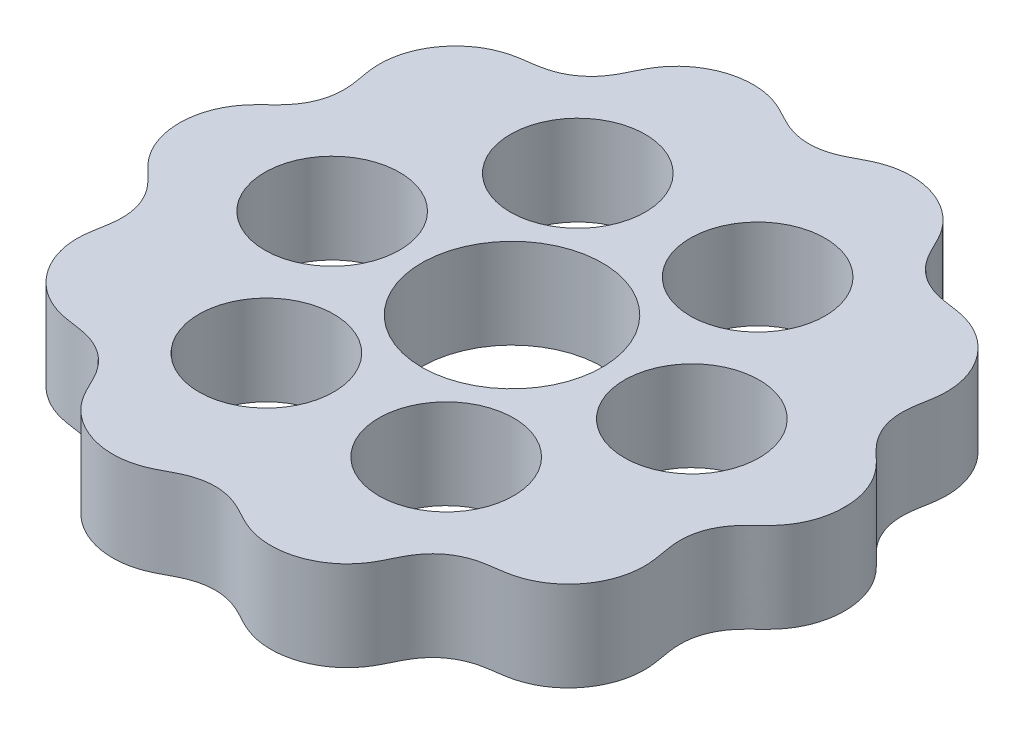
SolidWorks part; units mm, degrees
ref_plane "Front Plane" through (0, 0, 0) normal (0, 0, 1) x (1, 0, 0)
ref_plane "Top Plane" through (0, 0, 0) normal (0, 1, 0) x (1, 0, 0)
ref_plane "Right Plane" through (0, 0, 0) normal (1, 0, 0) x (0, 0, -1)
sketch "Sketch3" plane through (0, 0, 0) normal (0, 1, 0) x (1, 0, 0)
  line L0 (37, 0.0016) -> (37, 0)
  circle A8 centre (0, 0) radius 10.05
  circle A9 centre (20, 0.0013) radius 7.5
  circle A10 centre (10.0011, -17.3198) radius 7.5
  circle A11 centre (-9.9989, -17.3212) radius 7.5
  circle A12 centre (-20, -0.0013) radius 7.5
  circle A13 centre (-10.0011, 17.3198) radius 7.5
  circle A14 centre (9.9989, 17.3212) radius 7.5
  spline S0 degree 4 poles (35.9071, -20.9058) (35.9914, -20.646) (36.1459, -20.1219) (36.3345, -19.3236) (36.4974, -18.2422) (36.5702, -17.151) (36.5533, -16.0577) (36.455, -15.0177) (36.3162, -14.1457) (36.1841, -13.4361) (36.0999, -12.9253) (36.0584, -12.5653) (36.0496, -12.2224) (36.083, -11.8936) (36.188, -11.5721) (36.3627, -11.2777) (36.5928, -10.9853) (36.8654, -10.6961) (37.1851, -10.385) (37.5433, -10.0427) (38.0155, -9.5807) (38.5864, -8.9833) (39.2264, -8.2247) (39.8954, -7.2794) (40.3957, -6.4221) (40.7606, -5.6806) (41.0199, -5.0731) (41.1972, -4.6108) (41.3572, -4.1422) (41.4998, -3.6681) (41.6249, -3.1888) (41.7323, -2.7057) (41.8219, -2.2182) (41.8937, -1.7291) (41.9408, -1.2971) (41.97, -0.9276) (41.9852, -0.6533) (41.9925, -0.4614) (41.9976, -0.2622) (42.0004, -0.0689) (42.0004, 0.0868) (41.995, 0.4231) (41.98, 0.7903) (41.95, 1.2044) (41.8985, 1.6906) (41.83, 2.1667) (41.7445, 2.6443) (41.642, 3.1162) (41.5226, 3.5855) (41.3864, 4.0495) (41.2336, 4.5086) (41.0642, 4.9618) (40.8785, 5.4086) (40.6767, 5.8483) (40.4044, 6.3882) (40.0465, 7.0195) (39.5845, 7.7294) (38.9992, 8.5005) (38.3617, 9.229) (37.7471, 9.8506) (37.2345, 10.3361) (36.8495, 10.7125) (36.5753, 11.0078) (36.3656, 11.2699) (36.1909, 11.5665) (36.0759, 11.9257) (36.0454, 12.2689) (36.0624, 12.6048) (36.1118, 13.0057) (36.2028, 13.5376) (36.3321, 14.2334) (36.5001, 15.3392) (36.5994, 16.7927) (36.5088, 18.4932) (36.1215, 20.4) (35.4619, 22.2306) (34.5487, 23.946) (33.4033, 25.5131) (32.0493, 26.9009) (30.5132, 28.0808) (28.8229, 29.0266) (27.2386, 29.6295) (25.8309, 29.9783) (24.732, 30.1572) (24.0335, 30.2485) (23.5021, 30.327) (23.1077, 30.4056) (22.7852, 30.4957) (22.4708, 30.6351) (22.1686, 30.8608) (21.9438, 31.1223) (21.7609, 31.4055) (21.5656, 31.7601) (21.3266, 32.2452) (21.0213, 32.8855) (20.5051, 33.8807) (19.7274, 35.1165) (18.6497, 36.4399) (17.2094, 37.7547) (15.5934, 38.8465) (13.8338, 39.6976) (11.9667, 40.2905) (10.0292, 40.6113) (8.0612, 40.6482) (6.1086, 40.3964) (4.2154, 39.8563) (2.8138, 39.2258) (1.8483, 38.6935) (1.2513, 38.3822) (1.032, 38.2755) (0.7714, 38.1602) (0.4829, 38.0573) (0.1615, 37.9911) (-0.2151, 37.9987) (-0.5569, 38.0826) (-0.8789, 38.2097) (-1.259, 38.3909) (-1.7487, 38.6507) (-2.3805, 38.9927) (-3.389, 39.4921) (-4.7434, 40.0264) (-6.3905, 40.4541) (-8.324, 40.662) (-10.267, 40.5877) (-12.1841, 40.2363) (-14.0364, 39.6143) (-15.7856, 38.7323) (-17.393, 37.6039) (-18.8184, 36.2525) (-20.0268, 34.7041) (-20.7866, 33.3722) (-21.2531, 32.376) (-21.5803, 31.7205) (-21.7459, 31.4177) (-21.9435, 31.1084) (-22.208, 30.823) (-22.5189, 30.6105) (-22.846, 30.4795) (-23.1822, 30.3942) (-23.5974, 30.3181) (-24.1476, 30.2408) (-24.8613, 30.1456) (-25.9731, 29.9553) (-27.3855, 29.5884) (-28.9719, 28.9619) (-30.6599, 27.9876) (-32.1887, 26.7789) (-33.5306, 25.3624) (-34.6589, 23.7673) (-35.5496, 22.0251) (-36.181, 20.1701) (-36.5342, 18.2427) (-36.5909, 16.5288) (-36.4614, 15.0677) (-36.2805, 13.9849) (-36.1453, 13.2666) (-36.0602, 12.6842) (-36.0373, 12.2577) (-36.0858, 11.8743) (-36.2126, 11.5271) (-36.3935, 11.2391) (-36.6032, 10.9847) (-36.8748, 10.6964) (-37.2539, 10.3275) (-37.757, 9.8502) (-38.5279, 9.0704) (-39.4468, 7.9773) (-40.3619, 6.5813) (-41.1674, 4.8523) (-41.7186, 3.0266) (-42.01, 1.1315) (-42.0333, -0.7962) (-41.7832, -2.7182) (-41.258, -4.595) (-40.4662, -6.376) (-39.5519, -7.8159) (-38.6257, -8.9435) (-37.8386, -9.7515) (-37.3174, -10.2484) (-36.918, -10.6346) (-36.627, -10.9404) (-36.4053, -11.2071) (-36.2178, -11.5055) (-36.0914, -11.8602) (-36.0454, -12.2466) (-36.0675, -12.613) (-36.1117, -12.9552) (-36.2327, -13.6777) (-36.4416, -14.7577) (-36.6107, -16.2817) (-36.5445, -18.2447) (-36.1869, -20.1761) (-35.5509, -22.0341) (-34.6553, -23.7764) (-33.5235, -25.369) (-32.18, -26.7811) (-30.6525, -27.9842) (-28.9667, -28.9537) (-27.3831, -29.5768) (-25.9735, -29.9416) (-24.8642, -30.1311) (-24.152, -30.2262) (-23.6032, -30.3041) (-23.1892, -30.3812) (-22.854, -30.4678) (-22.5282, -30.6011) (-22.2193, -30.8165) (-21.9568, -31.1044) (-21.7603, -31.4152) (-21.5952, -31.7192) (-21.2684, -32.3767) (-20.8008, -33.3751) (-20.0383, -34.7095) (-18.8252, -36.26) (-17.3944, -37.6123) (-15.7813, -38.7402) (-14.0259, -39.6207) (-12.1673, -40.2397) (-10.2437, -40.5866) (-8.2946, -40.6545) (-6.3564, -40.4386) (-4.7063, -40.0025) (-3.3503, -39.4606) (-2.3475, -38.9596) (-1.7239, -38.6214) (-1.2451, -38.3697) (-0.8786, -38.1978) (-0.5642, -38.0764) (-0.2285, -37.9972) (0.1487, -37.9924) (0.4849, -38.0646) (0.7987, -38.1815) (1.1638, -38.3499) (1.6397, -38.5991) (2.2582, -38.9361) (3.2522, -39.4379) (4.5956, -39.984) (6.2314, -40.4285) (8.1546, -40.6581) (10.0908, -40.6077) (12.0022, -40.282) (13.8503, -39.6888) (15.598, -38.8388) (17.2084, -37.7465) (18.6434, -36.4324) (19.717, -35.1106) (20.4919, -33.8769) (21.0065, -32.8838) (21.3114, -32.245) (21.5506, -31.7614) (21.7465, -31.4081) (21.9304, -31.1265) (22.157, -30.8669) (22.4613, -30.644) (22.777, -30.507) (23.1007, -30.4183) (23.4962, -30.3408) (24.0289, -30.263) (24.7291, -30.1718) (25.8304, -29.9921) (27.241, -29.6412) (28.8281, -29.035) (30.5207, -28.0844) (32.0581, -26.899) (33.4107, -25.5067) (34.5526, -23.9371) (35.4611, -22.2216) (36.1158, -20.394) (36.4992, -18.4908) (36.5875, -16.7941) (36.4872, -15.344) (36.3191, -14.2407) (36.1904, -13.5464) (36.1004, -13.0156) (36.0524, -12.6154) (36.0371, -12.2802) (36.0702, -11.9376) (36.1886, -11.5794) (36.3657, -11.2839) (36.5771, -11.0223) (36.8529, -10.7272) (37.2393, -10.3505) (37.7533, -9.8641) (38.3691, -9.2409) (39.0075, -8.5102) (39.5933, -7.7369) (40.1214, -6.9231) (40.53, -6.1789) (40.8406, -5.521) (41.0723, -4.9609) (41.2413, -4.5065) (41.3937, -4.046) (41.5293, -3.5807) (41.648, -3.1102) (41.7498, -2.6369) (41.8345, -2.1581) (41.9022, -1.6808) (41.9527, -1.1934) (41.9818, -0.7782) (41.996, -0.4104) (42.0005, -0.0748) (42.0001, 0.1017) (41.9939, 0.436) (41.9781, 0.8027) (41.9472, 1.2157) (41.8947, 1.7009) (41.8253, 2.1759) (41.7389, 2.6524) (41.6357, 3.1232) (41.5156, 3.5913) (41.3788, 4.0541) (41.2254, 4.512) (41.0556, 4.9639) (40.8229, 5.5209) (40.5116, 6.175) (40.1025, 6.9149) (39.5743, 7.724) (38.9892, 8.4929) (38.3522, 9.2194) (37.7385, 9.8395) (37.2271, 10.3241) (36.8436, 10.7005) (36.571, 10.9963) (36.3634, 11.2592) (36.1856, 11.5678) (36.086, 11.905) (36.0574, 12.2165) (36.0688, 12.5602) (36.1119, 12.9211) (36.1975, 13.433) (36.3302, 14.1445) (36.4688, 15.019) (36.5661, 16.0618) (36.5813, 17.1582) (36.5063, 18.2522) (36.3407, 19.3362) (36.1497, 20.1362) (35.9935, 20.6613) (35.9084, 20.9216) knots 0 0 0 0 0 0.003453 0.006906 0.010359 0.013812 0.017264 0.020716 0.023554 0.024972 0.026391 0.027261 0.028132 0.029304 0.030549 0.031493 0.032437 0.034003 0.035569 0.037134 0.0387 0.042356 0.046012 0.049669 0.053325 0.05489 0.056454 0.058019 0.059584 0.061149 0.062713 0.064278 0.065843 0.067408 0.068973 0.069755 0.070538 0.070929 0.07132 0.072103 0.072867 0.073631 0.07516 0.076689 0.078218 0.079746 0.081275 0.082804 0.084333 0.085862 0.087391 0.08892 0.090449 0.091978 0.093506 0.096564 0.09962 0.102677 0.105736 0.108794 0.110668 0.111605 0.112542 0.113887 0.114906 0.115926 0.117275 0.118214 0.119153 0.121031 0.124097 0.127162 0.133289 0.139418 0.145548 0.151677 0.157806 0.163906 0.170007 0.17611 0.182211 0.188311 0.191362 0.194413 0.196283 0.197218 0.198153 0.199495 0.200511 0.201534 0.202886 0.203827 0.204768 0.20665 0.209723 0.212796 0.218936 0.225079 0.231223 0.237366 0.243508 0.249708 0.255908 0.262109 0.268309 0.274508 0.280708 0.281479 0.282249 0.28302 0.283791 0.285081 0.286117 0.28714 0.288515 0.289502 0.290489 0.292462 0.295524 0.298586 0.304711 0.310837 0.316961 0.323086 0.329211 0.335397 0.341582 0.34777 0.353955 0.36014 0.366326 0.367095 0.367864 0.369402 0.370689 0.371723 0.372748 0.374127 0.375115 0.376104 0.378082 0.381151 0.38422 0.390359 0.396498 0.402637 0.408775 0.414914 0.421085 0.427257 0.43343 0.439601 0.445772 0.448858 0.451944 0.453478 0.455013 0.456297 0.457328 0.458329 0.459651 0.460572 0.461493 0.463334 0.466338 0.469341 0.475351 0.481359 0.487368 0.493376 0.499384 0.505523 0.511661 0.5178 0.523939 0.530079 0.533148 0.536217 0.538194 0.539183 0.540172 0.541551 0.542576 0.543609 0.544897 0.546435 0.547204 0.547972 0.554158 0.560343 0.566529 0.572716 0.578901 0.585087 0.591212 0.597337 0.603461 0.609587 0.615712 0.618774 0.621837 0.62381 0.624796 0.625783 0.627159 0.628182 0.629217 0.630508 0.632049 0.63282 0.63359 0.639791 0.64599 0.652189 0.65839 0.66459 0.670789 0.676932 0.683075 0.689219 0.695362 0.701502 0.704575 0.707648 0.709531 0.710472 0.711413 0.712764 0.713787 0.714804 0.716146 0.717081 0.718015 0.719885 0.722936 0.725988 0.732088 0.738188 0.74429 0.750391 0.756492 0.762621 0.76875 0.77488 0.781009 0.787136 0.790202 0.793268 0.795146 0.796085 0.797024 0.798372 0.799393 0.800412 0.801757 0.802694 0.803631 0.805504 0.808563 0.811621 0.817735 0.823849 0.829965 0.83608 0.842195 0.84831 0.854425 0.860541 0.866656 0.87277 0.875828 0.878887 0.880761 0.881698 0.882635 0.88398 0.884999 0.886019 0.887368 0.888307 0.889246 0.891124 0.89419 0.897255 0.900318 0.903382 0.906446 0.90951 0.911043 0.912575 0.914108 0.91564 0.917172 0.918705 0.920237 0.921769 0.923301 0.924833 0.926365 0.927132 0.927898 0.92866 0.929423 0.930949 0.932475 0.934001 0.935526 0.937052 0.938578 0.940104 0.94163 0.943155 0.944681 0.946207 0.949259 0.95231 0.955362 0.958413 0.961465 0.964517 0.966388 0.967323 0.968258 0.969601 0.970617 0.971792 0.972665 0.973538 0.97496 0.976383 0.979228 0.982689 0.986151 0.989613 0.993075 0.996538 1 1 1 1 1 construction
  spline S1 degree 4 poles (42, 0) (42, 0.0517) (41.9993, 0.1553) (41.995, 0.4231) (41.98, 0.7903) (41.95, 1.2044) (41.8985, 1.6906) (41.83, 2.1667) (41.7445, 2.6443) (41.642, 3.1162) (41.5226, 3.5855) (41.3864, 4.0495) (41.2336, 4.5086) (41.0642, 4.9618) (40.8785, 5.4086) (40.6767, 5.8483) (40.4044, 6.3882) (40.0465, 7.0195) (39.5845, 7.7294) (38.9992, 8.5005) (38.3617, 9.229) (37.7471, 9.8506) (37.2345, 10.3361) (36.8495, 10.7125) (36.5753, 11.0078) (36.3656, 11.2699) (36.1909, 11.5665) (36.0759, 11.9257) (36.0454, 12.2689) (36.0624, 12.6048) (36.1118, 13.0057) (36.2028, 13.5376) (36.3321, 14.2334) (36.5001, 15.3392) (36.5994, 16.7927) (36.5088, 18.4932) (36.1215, 20.4) (35.4619, 22.2306) (34.5487, 23.946) (33.4033, 25.5131) (32.0493, 26.9009) (30.5132, 28.0808) (28.8229, 29.0266) (27.2386, 29.6295) (25.8309, 29.9783) (24.732, 30.1572) (24.0335, 30.2485) (23.5021, 30.327) (23.1077, 30.4056) (22.7852, 30.4957) (22.4708, 30.6351) (22.1686, 30.8608) (21.9438, 31.1223) (21.7609, 31.4055) (21.5656, 31.7601) (21.3266, 32.2452) (21.0213, 32.8855) (20.5051, 33.8807) (19.7274, 35.1165) (18.6497, 36.4399) (17.2094, 37.7547) (15.5934, 38.8465) (13.8338, 39.6976) (11.9667, 40.2905) (10.0292, 40.6113) (8.0612, 40.6482) (6.1086, 40.3964) (4.2154, 39.8563) (2.8138, 39.2258) (1.8483, 38.6935) (1.2513, 38.3822) (1.032, 38.2755) (0.7714, 38.1602) (0.4829, 38.0573) (0.1615, 37.9911) (-0.2151, 37.9987) (-0.5569, 38.0826) (-0.8789, 38.2097) (-1.259, 38.3909) (-1.7487, 38.6507) (-2.3805, 38.9927) (-3.389, 39.4921) (-4.7434, 40.0264) (-6.3905, 40.4541) (-8.324, 40.662) (-10.267, 40.5877) (-12.1841, 40.2363) (-14.0364, 39.6143) (-15.7856, 38.7323) (-17.393, 37.6039) (-18.8184, 36.2525) (-20.0268, 34.7041) (-20.7866, 33.3722) (-21.2531, 32.376) (-21.5803, 31.7205) (-21.7459, 31.4177) (-21.9435, 31.1084) (-22.208, 30.823) (-22.5189, 30.6105) (-22.846, 30.4795) (-23.1822, 30.3942) (-23.5974, 30.3181) (-24.1476, 30.2408) (-24.8613, 30.1456) (-25.9731, 29.9553) (-27.3855, 29.5884) (-28.9719, 28.9619) (-30.6599, 27.9876) (-32.1887, 26.7789) (-33.5306, 25.3624) (-34.6589, 23.7673) (-35.5496, 22.0251) (-36.181, 20.1701) (-36.5342, 18.2427) (-36.5909, 16.5288) (-36.4614, 15.0677) (-36.2805, 13.9849) (-36.1453, 13.2666) (-36.0602, 12.6842) (-36.0373, 12.2577) (-36.0858, 11.8743) (-36.2126, 11.5271) (-36.3935, 11.2391) (-36.6032, 10.9847) (-36.8748, 10.6964) (-37.2539, 10.3275) (-37.757, 9.8502) (-38.5279, 9.0704) (-39.4468, 7.9773) (-40.3619, 6.5813) (-41.1674, 4.8523) (-41.7186, 3.0266) (-42.01, 1.1315) (-42.0333, -0.7962) (-41.7832, -2.7182) (-41.258, -4.595) (-40.4662, -6.376) (-39.5519, -7.8159) (-38.6257, -8.9435) (-37.8386, -9.7515) (-37.3174, -10.2484) (-36.918, -10.6346) (-36.627, -10.9404) (-36.4053, -11.2071) (-36.2178, -11.5055) (-36.0914, -11.8602) (-36.0454, -12.2466) (-36.0675, -12.613) (-36.1117, -12.9552) (-36.2327, -13.6777) (-36.4416, -14.7577) (-36.6107, -16.2817) (-36.5445, -18.2447) (-36.1869, -20.1761) (-35.5509, -22.0341) (-34.6553, -23.7764) (-33.5235, -25.369) (-32.18, -26.7811) (-30.6525, -27.9842) (-28.9667, -28.9537) (-27.3831, -29.5768) (-25.9735, -29.9416) (-24.8642, -30.1311) (-24.152, -30.2262) (-23.6032, -30.3041) (-23.1892, -30.3812) (-22.854, -30.4678) (-22.5282, -30.6011) (-22.2193, -30.8165) (-21.9568, -31.1044) (-21.7603, -31.4152) (-21.5952, -31.7192) (-21.2684, -32.3767) (-20.8008, -33.3751) (-20.0383, -34.7095) (-18.8252, -36.26) (-17.3944, -37.6123) (-15.7813, -38.7402) (-14.0259, -39.6207) (-12.1673, -40.2397) (-10.2437, -40.5866) (-8.2946, -40.6545) (-6.3564, -40.4386) (-4.7063, -40.0025) (-3.3503, -39.4606) (-2.3475, -38.9596) (-1.7239, -38.6214) (-1.2451, -38.3697) (-0.8786, -38.1978) (-0.5642, -38.0764) (-0.2285, -37.9972) (0.1487, -37.9924) (0.4849, -38.0646) (0.7987, -38.1815) (1.1638, -38.3499) (1.6397, -38.5991) (2.2582, -38.9361) (3.2522, -39.4379) (4.5956, -39.984) (6.2314, -40.4285) (8.1546, -40.6581) (10.0908, -40.6077) (12.0022, -40.282) (13.8503, -39.6888) (15.598, -38.8388) (17.2084, -37.7465) (18.6434, -36.4324) (19.717, -35.1106) (20.4919, -33.8769) (21.0065, -32.8838) (21.3114, -32.245) (21.5506, -31.7614) (21.7465, -31.4081) (21.9304, -31.1265) (22.157, -30.8669) (22.4613, -30.644) (22.777, -30.507) (23.1007, -30.4183) (23.4962, -30.3408) (24.0289, -30.263) (24.7291, -30.1718) (25.8304, -29.9921) (27.241, -29.6412) (28.8281, -29.035) (30.5207, -28.0844) (32.0581, -26.899) (33.4107, -25.5067) (34.5526, -23.9371) (35.4611, -22.2216) (36.1158, -20.394) (36.4992, -18.4908) (36.5875, -16.7941) (36.4872, -15.344) (36.3191, -14.2407) (36.1904, -13.5464) (36.1004, -13.0156) (36.0524, -12.6154) (36.0371, -12.2802) (36.0702, -11.9376) (36.1886, -11.5794) (36.3657, -11.2839) (36.5771, -11.0223) (36.8529, -10.7272) (37.2393, -10.3505) (37.7533, -9.8641) (38.3691, -9.2409) (39.0075, -8.5102) (39.5933, -7.7369) (40.1214, -6.9231) (40.53, -6.1789) (40.8406, -5.521) (41.0723, -4.9609) (41.2413, -4.5065) (41.3937, -4.046) (41.5293, -3.5807) (41.648, -3.1102) (41.7498, -2.6369) (41.8345, -2.1581) (41.9022, -1.6808) (41.9527, -1.1934) (41.9818, -0.7782) (41.996, -0.4104) (41.9996, -0.1417) (42.0001, -0.038) (42, 0.0138) knots 0.072103 0.072103 0.072103 0.072103 0.072103 0.072867 0.073631 0.07516 0.076689 0.078218 0.079746 0.081275 0.082804 0.084333 0.085862 0.087391 0.08892 0.090449 0.091978 0.093506 0.096564 0.09962 0.102677 0.105736 0.108794 0.110668 0.111605 0.112542 0.113887 0.114906 0.115926 0.117275 0.118214 0.119153 0.121031 0.124097 0.127162 0.133289 0.139418 0.145548 0.151677 0.157806 0.163906 0.170007 0.17611 0.182211 0.188311 0.191362 0.194413 0.196283 0.197218 0.198153 0.199495 0.200511 0.201534 0.202886 0.203827 0.204768 0.20665 0.209723 0.212796 0.218936 0.225079 0.231223 0.237366 0.243508 0.249708 0.255908 0.262109 0.268309 0.274508 0.280708 0.281479 0.282249 0.28302 0.283791 0.285081 0.286117 0.28714 0.288515 0.289502 0.290489 0.292462 0.295524 0.298586 0.304711 0.310837 0.316961 0.323086 0.329211 0.335397 0.341582 0.34777 0.353955 0.36014 0.366326 0.367095 0.367864 0.369402 0.370689 0.371723 0.372748 0.374127 0.375115 0.376104 0.378082 0.381151 0.38422 0.390359 0.396498 0.402637 0.408775 0.414914 0.421085 0.427257 0.43343 0.439601 0.445772 0.448858 0.451944 0.453478 0.455013 0.456297 0.457328 0.458329 0.459651 0.460572 0.461493 0.463334 0.466338 0.469341 0.475351 0.481359 0.487368 0.493376 0.499384 0.505523 0.511661 0.5178 0.523939 0.530079 0.533148 0.536217 0.538194 0.539183 0.540172 0.541551 0.542576 0.543609 0.544897 0.546435 0.547204 0.547972 0.554158 0.560343 0.566529 0.572716 0.578901 0.585087 0.591212 0.597337 0.603461 0.609587 0.615712 0.618774 0.621837 0.62381 0.624796 0.625783 0.627159 0.628182 0.629217 0.630508 0.632049 0.63282 0.63359 0.639791 0.64599 0.652189 0.65839 0.66459 0.670789 0.676932 0.683075 0.689219 0.695362 0.701502 0.704575 0.707648 0.709531 0.710472 0.711413 0.712764 0.713787 0.714804 0.716146 0.717081 0.718015 0.719885 0.722936 0.725988 0.732088 0.738188 0.74429 0.750391 0.756492 0.762621 0.76875 0.77488 0.781009 0.787136 0.790202 0.793268 0.795146 0.796085 0.797024 0.798372 0.799393 0.800412 0.801757 0.802694 0.803631 0.805504 0.808563 0.811621 0.817735 0.823849 0.829965 0.83608 0.842195 0.84831 0.854425 0.860541 0.866656 0.87277 0.875828 0.878887 0.880761 0.881698 0.882635 0.88398 0.884999 0.886019 0.887368 0.888307 0.889246 0.891124 0.89419 0.897255 0.900318 0.903382 0.906446 0.90951 0.911043 0.912575 0.914108 0.91564 0.917172 0.918705 0.920237 0.921769 0.923301 0.924833 0.926365 0.927132 0.927898 0.927898 0.927898 0.927898 0.927898 construction
  spline S3 degree 3 poles (37, 0) (37, 0.0218) (36.9998, 0.0578) (36.998, 0.1899) (36.992, 0.404) (36.9768, 0.6592) (36.9432, 1.0077) (36.8543, 1.6544) (36.6208, 2.6428) (36.2004, 3.6575) (35.7716, 4.422) (35.4039, 4.9696) (34.9866, 5.4969) (34.5838, 5.9363) (34.2008, 6.3188) (33.8578, 6.649) (33.4219, 7.0685) (32.8147, 7.6897) (32.0281, 8.688) (31.4242, 9.984) (31.1417, 11.0511) (31.0461, 12.0015) (31.0631, 12.9935) (31.1724, 13.787) (31.2822, 14.419) (31.3696, 14.904) (31.4372, 15.3169) (31.5051, 15.8147) (31.5543, 16.3892) (31.5611, 17.0549) (31.5156, 17.7105) (31.3852, 18.578) (31.092, 19.6427) (30.5387, 20.8613) (29.8, 21.9838) (28.8976, 22.9776) (27.8581, 23.8133) (26.9027, 24.3587) (26.0945, 24.6992) (25.4667, 24.9068) (24.7989, 25.0722) (24.1899, 25.1795) (23.5811, 25.2658) (23.0182, 25.3424) (22.2238, 25.4712) (21.1262, 25.7427) (19.9176, 26.3204) (19.0089, 26.9629) (18.2781, 27.6939) (17.6173, 28.5642) (17.1854, 29.3408) (16.8809, 29.955) (16.6591, 30.4156) (16.4032, 30.9295) (16.1133, 31.4579) (15.7443, 32.0305) (15.3456, 32.555) (14.907, 33.0454) (14.2714, 33.6507) (13.3847, 34.3134) (12.1991, 34.9378) (10.9272, 35.3723) (9.6064, 35.6043) (8.497, 35.6231) (7.6222, 35.5338) (6.9766, 35.4151) (6.341, 35.2449) (5.7068, 35.0201) (5.1762, 34.7869) (4.7114, 34.5551) (4.3024, 34.3402) (3.8493, 34.0965) (3.165, 33.7442) (2.2468, 33.3449) (1.0518, 33.0562) (-0.0409, 32.9685) (-1.1208, 33.0709) (-2.2912, 33.3666) (-3.1941, 33.7657) (-3.8476, 34.1028) (-4.3175, 34.3562) (-4.711, 34.5629) (-5.1752, 34.7936) (-5.7096, 35.028) (-6.3415, 35.2511) (-6.9764, 35.4202) (-7.6237, 35.5384) (-8.4983, 35.6266) (-9.6074, 35.6062) (-10.9281, 35.3727) (-12.1998, 34.9365) (-13.3839, 34.3111) (-14.2706, 33.6466) (-14.9049, 33.041) (-15.3421, 32.5508) (-15.7413, 32.0244) (-16.1112, 31.4489) (-16.3969, 30.9266) (-16.6579, 30.4013) (-16.8492, 30.0075) (-17.0277, 29.6432) (-17.2867, 29.1449) (-17.6318, 28.5304) (-18.3198, 27.6405) (-19.0688, 26.9118) (-19.9838, 26.2844) (-21.1836, 25.729) (-22.2544, 25.4719) (-23.0348, 25.3466) (-23.5934, 25.2711) (-24.1959, 25.1854) (-24.8051, 25.0777) (-25.4706, 24.912) (-26.0988, 24.7034) (-26.906, 24.3621) (-27.861, 23.8153) (-28.8995, 22.9783) (-29.8008, 21.9833) (-30.538, 20.86) (-31.0898, 19.6407) (-31.3816, 18.5758) (-31.5109, 17.7083) (-31.5556, 17.0516) (-31.548, 16.3877) (-31.498, 15.8107) (-31.4293, 15.3107) (-31.362, 14.9002) (-31.2724, 14.4047) (-31.1632, 13.7686) (-31.0535, 12.9576) (-31.0448, 11.9402) (-31.1523, 10.981) (-31.4534, 9.9067) (-32.066, 8.6391) (-32.8419, 7.6688) (-33.4403, 7.0597) (-33.8704, 6.6466) (-34.2109, 6.3185) (-34.5929, 5.9366) (-34.9927, 5.4996) (-35.4108, 4.9701) (-35.7767, 4.4235) (-36.2051, 3.6581) (-36.6243, 2.6389) (-36.9322, 1.3385) (-37.0347, -0.0008) (-36.9289, -1.3398) (-36.6179, -2.6392) (-36.1961, -3.6572) (-35.7658, -4.4215) (-35.3985, -4.9672) (-34.9782, -5.4969) (-34.5771, -5.9335) (-34.1891, -6.3205) (-33.8458, -6.6509) (-33.4031, -7.078) (-32.787, -7.7104) (-31.9879, -8.7437) (-31.3978, -10.0572) (-31.1313, -11.1257) (-31.0485, -12.0574) (-31.0664, -12.7904) (-31.1174, -13.3276) (-31.2008, -13.9266) (-31.2902, -14.4171) (-31.3771, -14.9101) (-31.4454, -15.3264) (-31.5122, -15.8173) (-31.5605, -16.3906) (-31.5665, -17.0577) (-31.5202, -17.7136) (-31.389, -18.5791) (-31.0939, -19.6454) (-30.5395, -20.8623) (-29.7992, -21.9844) (-28.8956, -22.9768) (-27.8553, -23.8112) (-26.899, -24.3554) (-26.091, -24.6948) (-25.4616, -24.9019) (-24.7946, -25.0664) (-24.1812, -25.1738) (-23.5709, -25.2602) (-22.9988, -25.3384) (-22.1935, -25.4709) (-21.0724, -25.7553) (-19.8491, -26.3592) (-18.9507, -27.015) (-18.241, -27.7424) (-17.5967, -28.6082) (-17.2708, -29.1993) (-17.0229, -29.6823) (-16.8511, -30.0347) (-16.6619, -30.4247) (-16.4043, -30.9421) (-16.1185, -31.4622) (-15.748, -32.0356) (-15.3476, -32.5607) (-14.9092, -33.0498) (-14.2732, -33.6539) (-13.3847, -34.3163) (-12.199, -34.9388) (-10.9262, -35.372) (-9.605, -35.6022) (-8.496, -35.6197) (-7.6219, -35.5293) (-6.9749, -35.4095) (-6.3403, -35.2388) (-5.7082, -35.0139) (-5.1725, -34.7775) (-4.7053, -34.5445) (-4.3066, -34.3346) (-3.8269, -34.0765) (-3.1515, -33.7311) (-2.2021, -33.3228) (-0.9782, -33.0423) (0.1182, -32.9699) (1.1916, -33.0867) (2.332, -33.388) (3.2144, -33.7825) (3.8573, -34.1157) (4.3232, -34.367) (4.7138, -34.5722) (5.1763, -34.8015) (5.7107, -35.0352) (6.3419, -35.2572) (6.9772, -35.4255) (7.6246, -35.5428) (8.4994, -35.63) (9.6086, -35.6082) (10.9292, -35.373) (12.2, -34.9354) (13.3839, -34.3082) (14.2687, -33.6434) (14.9027, -33.0365) (15.34, -32.545) (15.7377, -32.0193) (16.106, -31.4447) (16.3961, -30.9135) (16.6547, -30.393) (16.8807, -29.9241) (17.1961, -29.2927) (17.6544, -28.4846) (18.3603, -27.5906) (19.1292, -26.8613) (20.0527, -26.2484) (21.2342, -25.7187) (22.2834, -25.4727) (23.0532, -25.3509) (23.6036, -25.2767) (24.2041, -25.1912) (24.8095, -25.0834) (25.4756, -24.9168) (26.1024, -24.7079) (26.9097, -24.3653) (27.8638, -23.8173) (28.9014, -22.9789) (29.8015, -21.9828) (30.5374, -20.8585) (31.0876, -19.6388) (31.3781, -18.5735) (31.5062, -17.7057) (31.55, -17.05) (31.5416, -16.3837) (31.491, -15.8078) (31.4218, -15.3071) (31.353, -14.8894) (31.2642, -14.3967) (31.1529, -13.7469) (31.0447, -12.9186) (31.0435, -11.8834) (31.1661, -10.9018) (31.4819, -9.8364) (32.1055, -8.5872) (32.8685, -7.6497) (33.4577, -7.0516) (33.8834, -6.6436) (34.2214, -6.318) (34.6003, -5.9385) (35.0009, -5.4999) (35.4163, -4.9724) (35.7825, -4.424) (36.2094, -3.6584) (36.6272, -2.6424) (36.8583, -1.6533) (36.9457, -1.0063) (36.9784, -0.6578) (36.993, -0.4025) (36.9984, -0.1882) (36.9999, -0.0561) (37, -0.0202) (37, 0.0016) knots 0.072103 0.072103 0.072103 0.072103 0.072521 0.072939 0.073774 0.075446 0.077117 0.078789 0.085475 0.09216 0.095503 0.098846 0.102189 0.105532 0.107204 0.108875 0.110547 0.112218 0.11389 0.114725 0.115561 0.116397 0.117233 0.118904 0.120576 0.122247 0.123919 0.12559 0.128933 0.132276 0.135619 0.138962 0.145648 0.152334 0.159019 0.165705 0.172391 0.179077 0.18242 0.185763 0.189106 0.192449 0.19412 0.195792 0.197463 0.199135 0.199971 0.200806 0.201642 0.202478 0.204149 0.205821 0.207492 0.209164 0.212507 0.21585 0.219193 0.222535 0.225878 0.232564 0.23925 0.245936 0.252622 0.259308 0.262651 0.265994 0.269337 0.27268 0.276023 0.277694 0.279366 0.281037 0.282709 0.28438 0.285216 0.286052 0.286887 0.287723 0.289394 0.291066 0.292737 0.294409 0.29608 0.299423 0.302766 0.306109 0.309452 0.312795 0.319481 0.326167 0.332853 0.339539 0.346225 0.349568 0.35291 0.356253 0.359596 0.362939 0.364611 0.366282 0.367118 0.367954 0.369625 0.370461 0.371297 0.372132 0.372968 0.37464 0.376311 0.377983 0.379654 0.382997 0.38634 0.389683 0.393026 0.399712 0.406398 0.413084 0.419769 0.426455 0.433141 0.436484 0.439827 0.44317 0.446513 0.448185 0.449856 0.451527 0.453199 0.45487 0.455706 0.456542 0.457378 0.458213 0.459885 0.461556 0.463228 0.464899 0.466571 0.469914 0.473257 0.4766 0.479943 0.486628 0.493314 0.5 0.506686 0.513372 0.520058 0.523401 0.526744 0.530087 0.53343 0.535101 0.536773 0.538444 0.540116 0.541787 0.542623 0.543459 0.544294 0.54513 0.545966 0.546801 0.548473 0.550144 0.551816 0.553487 0.55683 0.560173 0.563516 0.566859 0.573545 0.580231 0.586917 0.593603 0.600289 0.606975 0.610318 0.61366 0.617003 0.620346 0.622018 0.623689 0.625361 0.627032 0.627868 0.628704 0.629539 0.630375 0.632047 0.632882 0.633718 0.63539 0.637061 0.640404 0.643747 0.64709 0.650433 0.653776 0.660462 0.667148 0.673834 0.680519 0.687205 0.690548 0.693891 0.697234 0.700577 0.70392 0.705592 0.707263 0.708934 0.710606 0.712277 0.713113 0.713949 0.714785 0.71562 0.717292 0.718963 0.720635 0.722306 0.723978 0.727321 0.730664 0.734007 0.73735 0.740692 0.747378 0.754064 0.76075 0.767436 0.774122 0.777465 0.780808 0.784151 0.787494 0.790837 0.792508 0.79418 0.795851 0.797523 0.798358 0.799194 0.80003 0.800866 0.802537 0.804209 0.80588 0.807551 0.810894 0.814237 0.81758 0.820923 0.827609 0.834295 0.840981 0.847667 0.854353 0.861039 0.864382 0.867725 0.871067 0.87441 0.876082 0.877753 0.879425 0.881096 0.882768 0.883604 0.884439 0.885275 0.886111 0.887782 0.889454 0.891125 0.892797 0.894468 0.897811 0.901154 0.904497 0.90784 0.914526 0.921212 0.922883 0.924555 0.926226 0.927062 0.92748 0.927898 0.927898 0.927898 0.927898
  point P25 (0, 0)
  dimension "D2" = 20.1
  dimension "D3" = 15
  dimension "D4" = 20
  dimension "D5" = 6
extrude "Boss-Extrude1" add sketch "Sketch3" along normal blind 10
